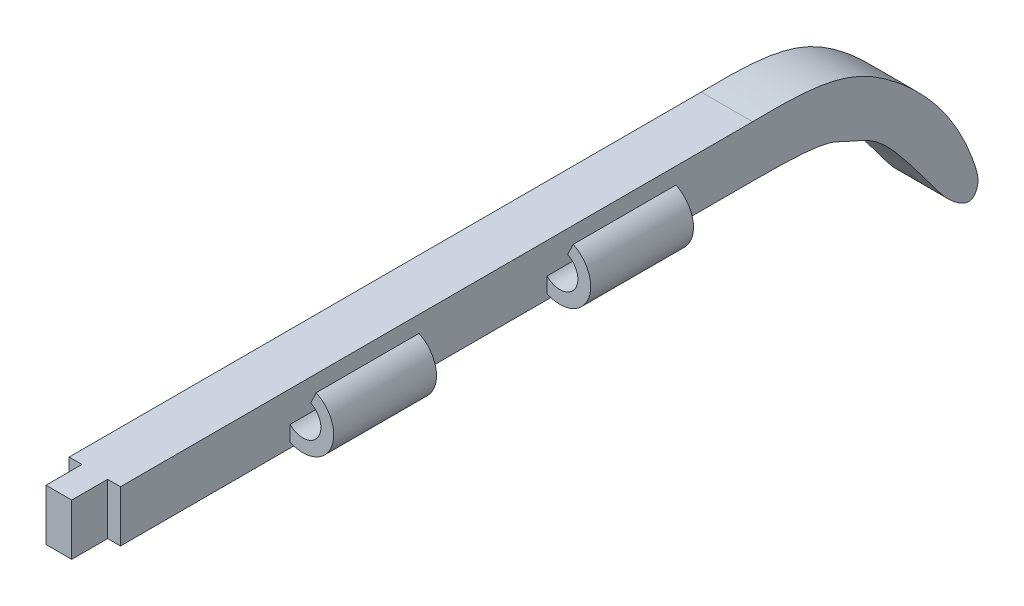
SolidWorks part; units mm, degrees
ref_plane "Front Plane" through (0, 0, 0) normal (0, 0, 1) x (1, 0, 0)
ref_plane "Top Plane" through (0, 0, 0) normal (0, 1, 0) x (1, 0, 0)
ref_plane "Right Plane" through (0, 0, 0) normal (1, 0, 0) x (0, 0, -1)
sketch "Sketch3" plane through (0, 0, 0) normal (1, 0, 0) x (0, 0, -1)
  line L2 (0, 10) -> (130, 10)
  line L4 (0, 0) -> (0, 10)
  line L6 (130, 0) -> (0, 0)
  spline S0 degree 3 poles (130, 10) (143.2578, 10.296) (152.3626, 8.4113) (167.4786, -5.7733) (172.6159, -16.2821) (174.0748, -21.8732) (172.8579, -25.2751) (168.5616, -23.1552) (157.0615, -7.4485) (154.6005, -5.1266) (145.2323, -1.2395) (144.4774, 0) (130, 0) knots 0 0 0 0 0.101519 0.157911 0.210542 0.223356 0.22806 0.254301 0.29921 0.632235 0.706477 1 1 1 1
  dimension "D1" = 130
  dimension "D5" = 10
ref_plane "Plane3" through (0, 0, -50) normal (0, 0, 1) x (1, 0, 0)
ref_plane "Plane4" through (0, 0, -75) normal (0, 0, 1) x (1, 0, 0)
extrude "Boss-Extrude1" add sketch "Sketch3" along normal blind 10 contours L2 S0 L6 L4
sketch "Sketch6" plane through (0, 0, -50) normal (0, 0, 1) x (1, 0, 0)
  line L2 (15.0776, 11.8723) -> (14, 9.6165)
  line L4 (10, 0) -> (10, 10) construction
  line L5 (10.9826, 3.3002) -> (16.0862, 13.9835) construction
  line L6 (10, 0) -> (10, 10)
  line L7 (10, -24.4871) -> (10, 10.0418) construction
  arc A0 (10, 1) -> (15.0776, 11.8723) centre (12.4913, 6.4583) ccw
  arc A2 (10, 4) -> (14, 9.6165) centre (12.4913, 6.4583) ccw
  dimension "D1" = 6
  dimension "D3" = 4
  dimension "D2" = 3
  dimension "D4" = 3.5
  dimension "D5" = 1
extrude "Boss-Extrude2" add sketch "Sketch6" against normal mid plane 20 contours A2 L6 A0 L2
mirror "Mirror4" about plane through (0, 0, -75) normal (0, 0, 1) of "Boss-Extrude2"
sketch "Sketch7" plane through (0, 0, 0) normal (0, 0, 1) x (1, 0, 0)
  line L0 (10, 10) -> (0, 10) construction
  line L1 (2.5, 10) -> (7.5, 10)
  line L2 (2.5, 10) -> (2.5, 0)
  line L3 (2.5, 0) -> (7.5, 0)
  line L4 (7.5, 10) -> (7.5, 0)
  line L5 (10, 0) -> (0, 0) construction
  line L6 (10, 0) -> (10, 10) construction
  line L7 (0, 0) -> (0, 10) construction
  line L8 (10, 10) -> (0, 10) construction
  line L9 (10, 0) -> (10, 10)
  line L10 (10, 0) -> (0, 0)
  line L11 (0, 0) -> (0, 10)
  line L12 (10, 10) -> (0, 10)
  point P8 (5, 10)
  point P9 (5, 10)
  line M5 (0, 10) -> (0, 0)
  line M6 (0, 0) -> (10, 0)
  line M7 (10, 0) -> (10, 10)
  line M8 (10, 10) -> (0, 10)
  dimension "D1" = 5
extrude "Cut-Extrude1" cut sketch "Sketch7" against normal blind 7 contours L4 M8 M6 M7 | L2 M8 M5 M6 | L9 L12 L11 L10
